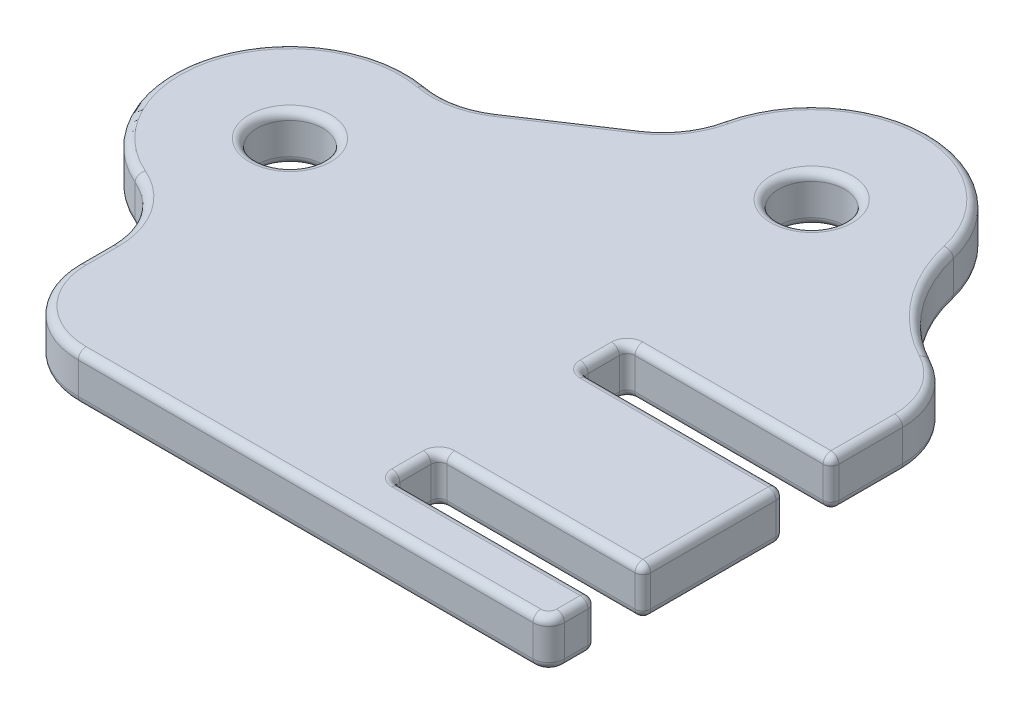
SolidWorks part; units mm, degrees
ref_plane "Front Plane" through (0, 0, 0) normal (0, 0, 1) x (1, 0, 0)
ref_plane "Top Plane" through (0, 0, 0) normal (0, 1, 0) x (1, 0, 0)
ref_plane "Right Plane" through (0, 0, 0) normal (1, 0, 0) x (0, 0, -1)
sketch "Sketch1" plane through (0, 0, 0) normal (0, 1, 0) x (1, 0, 0)
  line L0 (0, -11.4564) -> (0, -18.5)
  line L1 (0, -18.5) -> (30, -18.5)
  line L2 (30, -18.5) -> (30, -10.9559)
  line L3 (29.0642, -8.3847) -> (22.592, -0.6715)
  line L4 (0, 0) -> (20, 13.2665) construction
  line L5 (5.0178, 8.1284) -> (10.56, 11.8047)
  line L7 (-2.2111, 3.3333) -> (17.7889, 16.5998) construction
  circle A0 centre (0, 0) radius 2.1
  arc A1 (1.3524, 7.3771) -> (-3, -6.8739) centre (0, 0) ccw
  circle A2 centre (20, 13.2665) radius 2.1
  arc A3 (23.8533, 6.8321) -> (12.6777, 14.8894) centre (20, 13.2665) ccw
  arc A4 (5.0178, 8.1284) -> (1.3524, 7.3771) centre (2.254, 12.2951) cw
  arc A5 (10.56, 11.8047) -> (12.6777, 14.8894) centre (7.7962, 15.9714) ccw
  arc A6 (22.592, -0.6715) -> (23.8533, 6.8321) centre (26.4222, 2.5425) cw
  arc A7 (0, -11.4564) -> (-3, -6.8739) centre (-5, -11.4564) ccw
  arc A8 (30, -10.9559) -> (29.0642, -8.3847) centre (26, -10.9559) ccw
  point P26 (0, -7.5)
  point P29 (30, -9.5)
  dimension "D1" = 4.2
  dimension "D2" = 15
  dimension "D3" = 4.2
  dimension "D4" = 15
  dimension "D12" = 5
  dimension "D13" = 5
  dimension "D14" = 5
  dimension "D15" = 5
  dimension "D16" = 4
  dimension "D5" = 24
  dimension "D6" = 20
  dimension "D7" = 11
  dimension "D8" = 30
  dimension "D9" = 9
  dimension "D10" = 50
  dimension "D11" = 4
extrude "Boss-Extrude1" add sketch "Sketch1" along normal blind 3
fillet "Fillet1" radius 5 1 edges at (0, 1.5, 18.5)
sketch "Sketch2" plane through (0, 3, 0) normal (0, 1, 0) x (1, 0, 0)
  line L0 (30, -18.5) -> (30, -10.9559) construction
  line L1 (30, -12.5) -> (22, -12.5)
  line L2 (30, -12.5) -> (30, -15.5)
  line L3 (30, -15.5) -> (22, -15.5)
  line L4 (22, -12.5) -> (22, -15.5)
  line L5 (5, -18.5) -> (30, -18.5) construction
  dimension "D1" = 3
  dimension "D2" = 8
  dimension "D3" = 3
extrude "Cut-Extrude1" cut sketch "Sketch2" against normal blind 3
sketch "Sketch3" plane through (0, 3, 0) normal (0, 1, 0) x (1, 0, 0)
  line L0 (22, -12.5) -> (22, -15.5) construction
  line L1 (32, -0.5) -> (22, -0.5)
  line L2 (32, -0.5) -> (32, -3.5)
  line L3 (32, -3.5) -> (22, -3.5)
  line L4 (22, -0.5) -> (22, -3.5)
  line L5 (22, -15.5) -> (30, -15.5) construction
  dimension "D1" = 3
  dimension "D2" = 10
  dimension "D3" = 12
sketch "Sketch4" plane through (0, 3, 0) normal (0, 1, 0) x (1, 0, 0)
  line L0 (27.1269, 10.9305) -> (35, 7.21)
  line L1 (35, 7.21) -> (35, -0.5)
  line L2 (35, -18.5) -> (18.1019, -18.5)
  line L3 (5, -18.5) -> (30, -18.5) construction
  line L4 (18.1019, -18.5) -> (15.5268, 5.2656)
  line L5 (15.5268, 5.2656) -> (27.1269, 10.9305)
  line L7 (22, -12.5) -> (22, -15.5) construction
  line L8 (35, -15.5) -> (35, -18.5)
  line L9 (22, -12.5) -> (35, -12.5)
  line L10 (22, -12.5) -> (22, -15.5)
  line L11 (22, -15.5) -> (35, -15.5)
  line L12 (35, -3.5) -> (35, -12.5)
  line L13 (22, -3.5) -> (35, -3.5)
  line L14 (22, -3.5) -> (22, -0.5)
  line L15 (22, -0.5) -> (35, -0.5)
  arc A0 (23.8533, 6.8321) -> (12.6777, 14.8894) centre (20, 13.2665) ccw construction
  dimension "D1" = 13
  dimension "D2" = 3
  dimension "D3" = 3
extrude "Boss-Extrude2" add sketch "Sketch4" against normal blind 3
fillet "Fillet2" radius 10 1 edges at (27.1269, 1.5, -10.9305)
sketch "Sketch5" plane through (0, 3, 0) normal (0, 1, 0) x (1, 0, 0)
  line L1 (35, -0.5) -> (22, -0.5)
  line L2 (35, -0.5) -> (35, -3.5)
  line L3 (35, -3.5) -> (22, -3.5)
  line L4 (22, -0.5) -> (22, -3.5)
  dimension "D1" = 3
  dimension "D2" = 13
extrude "Cut-Extrude3" cut sketch "Sketch5" against normal blind 3.5
fillet "Fillet3" radius 5 1 edges at (35, 1.5, -7.21)
fillet "Fillet4" radius 1 1 edges at (35, 1.5, 18.5)
sketch "Sketch6" plane through (0, 3, 0) normal (0, 1, 0) x (1, 0, 0)
  line L0 (25.925, -10.5934) -> (-0.075, -10.5934) construction
  arc A0 (0, -11.4564) -> (-3, -6.8739) centre (-5, -11.4564) ccw construction
  text T0 "pax" font "Airstrike" height in points 20
  dimension "D1" = 26
fillet "Fillet5" radius 0.5 54 edges at (35, 3, 16.5) (35, 0, 16.5) (34.7071, 0, 18.2071) (19.5, 0, 18.5) (1.4645, 0, 17.0355) (0, 0, 12.4782) (-0.8167, 0, 8.7178) (-7.1729, 0, -2.1907) (3.258, 0, -7.397) (7.7889, 0, -9.9666) (11.9183, 0, -13.1415) (19.9429, 0, -20.7663) (35, 0, -1.7801) (35, 3, -1.7801) (34.2842, 0, -6.638) (34.2842, 3, -6.638) (34.7071, 3, 18.2071) (19.5, 3, 18.5) (1.4645, 3, 17.0355) (0, 3, 12.4782) (-0.8167, 3, 8.7178) (-7.1729, 3, -2.1907) (3.258, 3, -7.397) (7.7889, 3, -9.9666) (11.9183, 3, -13.1415) (19.9429, 3, -20.7663) (28.5, 3, 15.5) (28.5, 0, 15.5) (35, 1.5, 15.5) (22, 0, 14) (22, 1.5, 15.5) (22, 3, 14) (28.5, 3, 12.5) (28.5, 0, 12.5) (22, 1.5, 12.5) (35, 3, 8) (35, 0, 8) (35, 1.5, 12.5) (35, 1.5, 3.5) (28.5, 0, 3.5) (28.5, 3, 3.5) (35, 1.5, 0.5) (28.5, 3, 0.5) (28.5, 0, 0.5) (22, 1.5, 3.5) (22, 3, 2) (22, 1.5, 0.5) (22, 0, 2) (0, 0, 2.1) (0, 3, 2.1) (20, 0, -11.1665) (20, 3, -11.1665) (29.1156, 0, -11.195) (29.1156, 3, -11.195)
